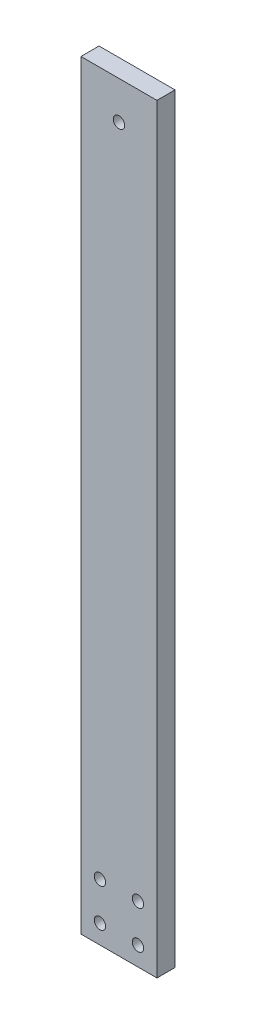
SolidWorks part; units mm, degrees
ref_plane "Front Plane" through (0, 0, 0) normal (0, 0, 1) x (1, 0, 0)
ref_plane "Top Plane" through (0, 0, 0) normal (0, 1, 0) x (1, 0, 0)
ref_plane "Right Plane" through (0, 0, 0) normal (1, 0, 0) x (0, 0, -1)
sketch "Sketch1" plane through (0, 0, 0) normal (0, 0, 1) x (1, 0, 0)
  line L1 (-10, -100) -> (10, -100)
  line L2 (-10, -100) -> (-10, 100)
  line L3 (-10, 100) -> (10, 100)
  line L4 (10, -100) -> (10, 100)
  line L5 (-10, -100) -> (10, 100) construction
  line L6 (-10, 100) -> (10, -100) construction
  point P0 (0, 0)
  dimension "D1" = 20
  dimension "D2" = 200
extrude "Boss-Extrude1" add sketch "Sketch1" along normal blind 4.7625
sketch "Sketch2" plane through (0, 0, 4.7625) normal (0, 0, 1) x (1, 0, 0)
  line L0 (-10, -100) -> (10, -100) construction
  line L1 (-10, 100) -> (-10, -100) construction
  circle A0 centre (-5, -95) radius 1.5
  circle A1 centre (5, -95) radius 1.5
  circle A2 centre (-5, -85) radius 1.5
  circle A3 centre (5, -85) radius 1.5
  dimension "D1" = 3
  dimension "D2" = 3
  dimension "D3" = 3
  dimension "D4" = 3
  dimension "D5" = 10
  dimension "D6" = 10
  dimension "D7" = 10
  dimension "D8" = 5
  dimension "D9" = 5
  dimension "D10" = 10
  dimension "D11" = 5
  dimension "D12" = 10
extrude "Cut-Extrude1" cut sketch "Sketch2" against normal through all
sketch "Sketch3" plane through (0, 0, 4.7625) normal (0, 0, 1) x (1, 0, 0)
  line L0 (10, 100) -> (-10, 100) construction
  line L1 (-10, 100) -> (-10, -100) construction
  circle A0 centre (0, 90) radius 1.5
  dimension "D1" = 3
  dimension "D2" = 10
  dimension "D3" = 10
extrude "Cut-Extrude2" cut sketch "Sketch3" against normal through all
